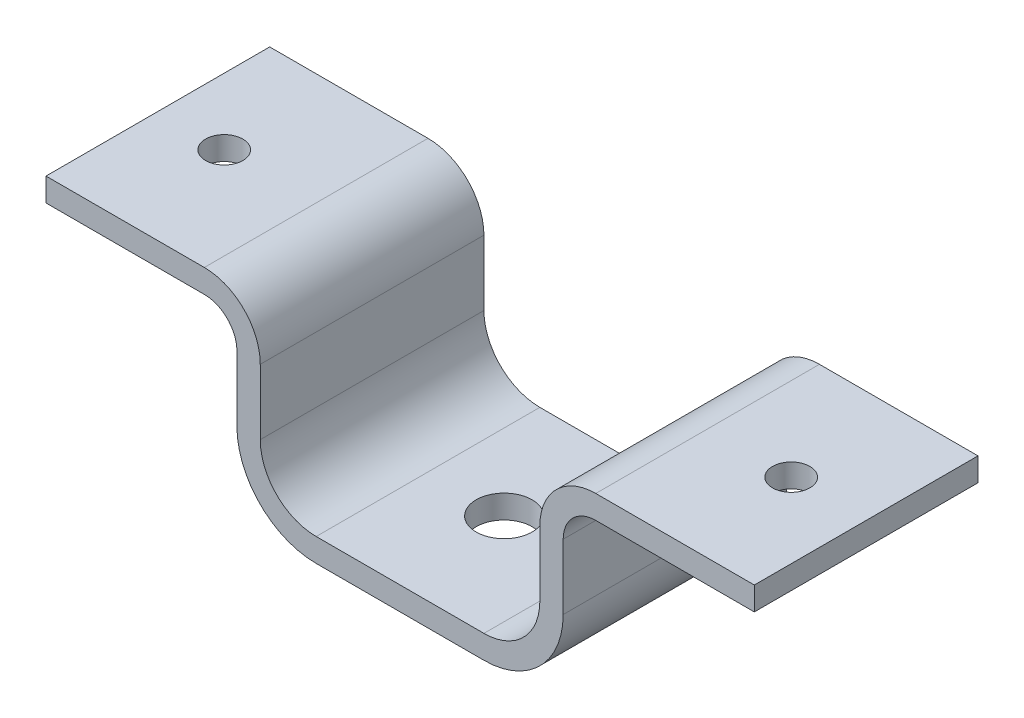
SolidWorks part; units mm, degrees
ref_plane "Front Plane" through (0, 0, 0) normal (0, 0, 1) x (1, 0, 0)
ref_plane "Top Plane" through (0, 0, 0) normal (0, 1, 0) x (1, 0, 0)
ref_plane "Right Plane" through (0, 0, 0) normal (1, 0, 0) x (0, 0, -1)
sketch "Sketch3" plane through (0, 0, 0) normal (0, 0, 1) x (1, 0, 0)
  line L0 (-308.4738, 97.6836) -> (-254.536, 97.6836)
  line L1 (-235.486, 78.6336) -> (-235.486, 56.4086)
  line L2 (-216.436, 37.3586) -> (-159.286, 37.3586)
  line L3 (-140.236, 56.4086) -> (-140.236, 78.6336)
  line L4 (-121.186, 97.6836) -> (-67.1738, 97.6836)
  line L5 (-308.4738, 89.7334) -> (-254.536, 89.7334)
  line L6 (-243.4362, 78.6336) -> (-243.4362, 56.4086)
  line L7 (-216.436, 29.4084) -> (-159.286, 29.4084)
  line L8 (-132.2858, 56.4086) -> (-132.2858, 78.6336)
  line L9 (-121.186, 89.7334) -> (-67.1738, 89.7334)
  line L10 (-308.4738, 97.6836) -> (-308.4738, 89.7334)
  line L11 (-67.1738, 97.6836) -> (-67.1738, 89.7334)
  arc A0 (-254.536, 97.6836) -> (-235.486, 78.6336) centre (-254.536, 78.6336) cw
  arc A1 (-140.236, 78.6336) -> (-121.186, 97.6836) centre (-121.186, 78.6336) cw
  arc A2 (-159.286, 37.3586) -> (-140.236, 56.4086) centre (-159.286, 56.4086) ccw
  arc A3 (-235.486, 56.4086) -> (-216.436, 37.3586) centre (-216.436, 56.4086) ccw
  arc A4 (-254.536, 89.7334) -> (-243.4362, 78.6336) centre (-254.536, 78.6336) cw
  arc A5 (-243.4362, 56.4086) -> (-216.436, 29.4084) centre (-216.436, 56.4086) ccw
  arc A6 (-159.286, 29.4084) -> (-132.2858, 56.4086) centre (-159.286, 56.4086) ccw
  arc A7 (-132.2858, 78.6336) -> (-121.186, 89.7334) centre (-121.186, 78.6336) cw
  point P11 (-235.486, 97.6836)
  point P14 (-140.236, 97.6836)
  point P19 (-235.486, 37.3586)
  dimension "D4" = 19.05
  dimension "D1" = 241.3
  dimension "D2" = 60.325
  dimension "D3" = 95.25
  dimension "D5" = 7.9502
extrude "Boss-Extrude1" add sketch "Sketch3" along normal mid plane 76.2
sketch "Sketch4" plane through (0, 97.6836, 0) normal (0, 1, 0) x (1, 0, 0)
  circle A0 centre (-190.5, 0) radius 9.525
  circle A1 centre (-285.8597, 0) radius 6.35
  circle A2 centre (-92.7105, 0) radius 6.35
  dimension "D1" = 12.7
  dimension "D2" = 19.05
extrude "Cut-Extrude1" cut sketch "Sketch4" against normal blind 76.2
